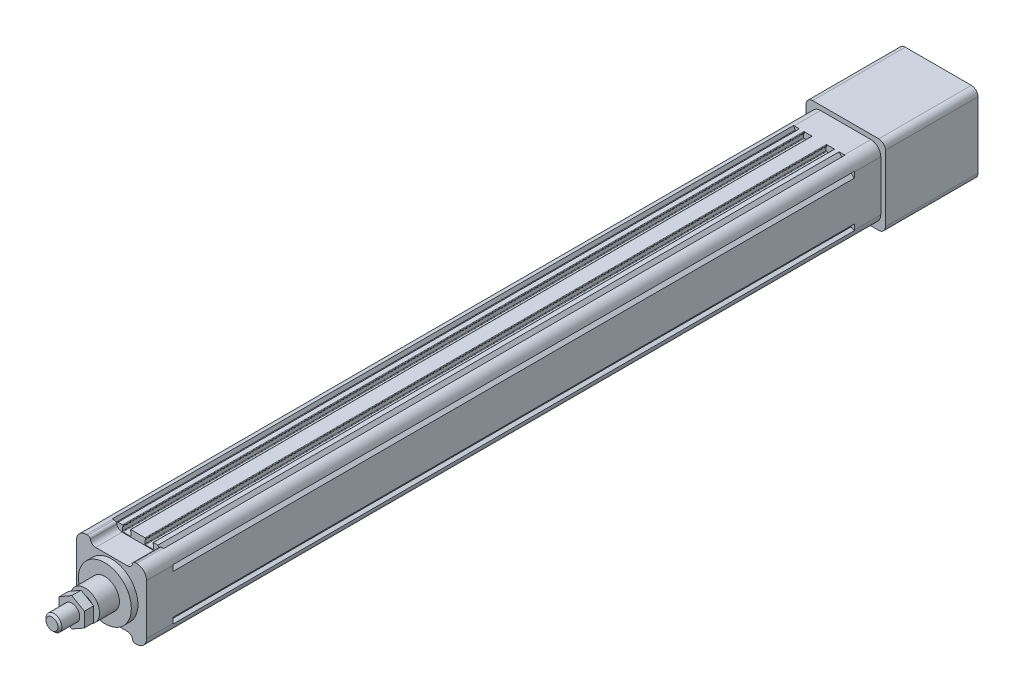
SolidWorks part; units mm, degrees
ref_plane "Front" through (0, 0, 0) normal (0, 0, 1) x (1, 0, 0)
ref_plane "Top" through (0, 0, 0) normal (0, 1, 0) x (1, 0, 0)
ref_plane "Right" through (0, 0, 0) normal (1, 0, 0) x (0, 0, -1)
sketch "草图1" plane through (0, 0, 0) normal (0, 0, 1) x (1, 0, 0)
  line L0 (19.7737, 3) -> (23.3, 3)
  line L1 (23.3, 3) -> (23.3, -3)
  line L2 (23.3, -3) -> (19.7737, -3)
  line L3 (-19.7737, -3) -> (-23.3, -3)
  line L4 (-23.3, -3) -> (-23.3, 3)
  line L5 (-23.3, 3) -> (-19.7737, 3)
  line L6 (-18.2, 24) -> (-19.4434, 26.4869)
  line L7 (-26.4869, 19.4434) -> (-24, 18.2)
  line L8 (-24, 18.2) -> (-24, 17.1)
  line L9 (-24, 17.1) -> (-26.5, 15)
  line L10 (-26.5, 15) -> (-26.5, -15)
  line L11 (-26.5, -15) -> (-24, -17.1)
  line L12 (-24, -17.1) -> (-24, -18.2)
  line L13 (-24, -18.2) -> (-26.4869, -19.4434)
  line L14 (-19.4434, -26.4869) -> (-18.2, -24)
  line L15 (-18.2, -24) -> (-17.1, -24)
  line L16 (-17.1, -24) -> (-15, -26.5)
  line L17 (-15, -26.5) -> (-11.65, -26.5)
  line L18 (-11.25, -26.1) -> (-11.25, -25.6)
  line L19 (-11.65, -25.2) -> (-11.75, -25.2)
  line L20 (-11.75, -25.2) -> (-11.75, -22.4)
  line L21 (-11.35, -22) -> (-5.65, -22)
  line L22 (-5.25, -22.4) -> (-5.25, -25.2)
  line L23 (-5.25, -25.2) -> (-5.35, -25.2)
  line L24 (-5.75, -25.6) -> (-5.75, -26.1)
  line L25 (-5.35, -26.5) -> (5.35, -26.5)
  line L26 (5.75, -26.1) -> (5.75, -25.6)
  line L27 (5.35, -25.2) -> (5.25, -25.2)
  line L28 (5.25, -25.2) -> (5.25, -22.4)
  line L29 (5.65, -22) -> (11.35, -22)
  line L30 (11.75, -22.4) -> (11.75, -25.2)
  line L31 (11.75, -25.2) -> (11.65, -25.2)
  line L32 (11.25, -25.6) -> (11.25, -26.1)
  line L33 (11.65, -26.5) -> (15, -26.5)
  line L34 (15, -26.5) -> (17.1, -24)
  line L35 (17.1, -24) -> (18.2, -24)
  line L36 (18.2, -24) -> (19.4434, -26.4869)
  line L37 (26.4869, -19.4434) -> (24, -18.2)
  line L38 (24, -18.2) -> (24, -17.1)
  line L39 (24, -17.1) -> (26.5, -15)
  line L40 (26.5, -15) -> (26.5, 15)
  line L41 (26.5, 15) -> (24, 17.1)
  line L42 (24, 17.1) -> (24, 18.2)
  line L43 (24, 18.2) -> (26.4869, 19.4434)
  line L44 (19.4434, 26.4869) -> (18.2, 24)
  line L45 (18.2, 24) -> (17.1, 24)
  line L46 (17.1, 24) -> (15, 26.5)
  line L47 (15, 26.5) -> (11.65, 26.5)
  line L48 (11.25, 26.1) -> (11.25, 25.6)
  line L49 (11.65, 25.2) -> (11.75, 25.2)
  line L50 (11.75, 25.2) -> (11.75, 22.4)
  line L51 (11.35, 22) -> (5.65, 22)
  line L52 (5.25, 22.4) -> (5.25, 25.2)
  line L53 (5.25, 25.2) -> (5.35, 25.2)
  line L54 (5.75, 25.6) -> (5.75, 26.1)
  line L55 (5.35, 26.5) -> (-5.35, 26.5)
  line L56 (-5.75, 26.1) -> (-5.75, 25.6)
  line L57 (-5.35, 25.2) -> (-5.25, 25.2)
  line L58 (-5.25, 25.2) -> (-5.25, 22.4)
  line L59 (-5.65, 22) -> (-11.35, 22)
  line L60 (-11.75, 22.4) -> (-11.75, 25.2)
  line L61 (-11.75, 25.2) -> (-11.65, 25.2)
  line L62 (-11.25, 25.6) -> (-11.25, 26.1)
  line L63 (-11.65, 26.5) -> (-15, 26.5)
  line L64 (-15, 26.5) -> (-17.1, 24)
  line L65 (-17.1, 24) -> (-18.2, 24)
  arc A0 (19.7737, 3) -> (-19.7737, 3) centre (0, 0) ccw
  arc A1 (-19.7737, -3) -> (19.7737, -3) centre (0, 0) ccw
  circle A2 centre (19, 19) radius 2.1
  circle A3 centre (19, -19) radius 2.1
  circle A4 centre (-19, -19) radius 2.1
  circle A5 centre (-19, 19) radius 2.1
  arc A6 (-19.4434, 26.4869) -> (-26.4869, 19.4434) centre (-19, 19) ccw
  arc A7 (-26.4869, -19.4434) -> (-19.4434, -26.4869) centre (-19, -19) ccw
  arc A8 (-11.65, -26.5) -> (-11.25, -26.1) centre (-11.65, -26.1) ccw
  arc A9 (-11.25, -25.6) -> (-11.65, -25.2) centre (-11.65, -25.6) ccw
  arc A10 (-11.35, -22) -> (-11.75, -22.4) centre (-11.35, -22.4) ccw
  arc A11 (-5.25, -22.4) -> (-5.65, -22) centre (-5.65, -22.4) ccw
  arc A12 (-5.35, -25.2) -> (-5.75, -25.6) centre (-5.35, -25.6) ccw
  arc A13 (-5.75, -26.1) -> (-5.35, -26.5) centre (-5.35, -26.1) ccw
  arc A14 (5.35, -26.5) -> (5.75, -26.1) centre (5.35, -26.1) ccw
  arc A15 (5.75, -25.6) -> (5.35, -25.2) centre (5.35, -25.6) ccw
  arc A16 (5.65, -22) -> (5.25, -22.4) centre (5.65, -22.4) ccw
  arc A17 (11.75, -22.4) -> (11.35, -22) centre (11.35, -22.4) ccw
  arc A18 (11.65, -25.2) -> (11.25, -25.6) centre (11.65, -25.6) ccw
  arc A19 (11.25, -26.1) -> (11.65, -26.5) centre (11.65, -26.1) ccw
  arc A20 (19.4434, -26.4869) -> (26.4869, -19.4434) centre (19, -19) ccw
  arc A21 (26.4869, 19.4434) -> (19.4434, 26.4869) centre (19, 19) ccw
  arc A22 (11.65, 26.5) -> (11.25, 26.1) centre (11.65, 26.1) ccw
  arc A23 (11.25, 25.6) -> (11.65, 25.2) centre (11.65, 25.6) ccw
  arc A24 (11.35, 22) -> (11.75, 22.4) centre (11.35, 22.4) ccw
  arc A25 (5.25, 22.4) -> (5.65, 22) centre (5.65, 22.4) ccw
  arc A26 (5.35, 25.2) -> (5.75, 25.6) centre (5.35, 25.6) ccw
  arc A27 (5.75, 26.1) -> (5.35, 26.5) centre (5.35, 26.1) ccw
  arc A28 (-5.35, 26.5) -> (-5.75, 26.1) centre (-5.35, 26.1) ccw
  arc A29 (-5.75, 25.6) -> (-5.35, 25.2) centre (-5.35, 25.6) ccw
  arc A30 (-5.65, 22) -> (-5.25, 22.4) centre (-5.65, 22.4) ccw
  arc A31 (-11.75, 22.4) -> (-11.35, 22) centre (-11.35, 22.4) ccw
  arc A32 (-11.65, 25.2) -> (-11.25, 25.6) centre (-11.65, 25.6) ccw
  arc A33 (-11.25, 26.1) -> (-11.65, 26.5) centre (-11.65, 26.1) ccw
extrude "凸台-拉伸1" add sketch "草图1" along normal blind 515
sketch "草图6" plane through (0, 0, 515) normal (0, 0, 1) x (1, 0, 0)
  line L0 (0, 0) -> (19, 0) construction
  line L2 (-26.5, -19) -> (-26.5, 19)
  line L3 (-19, 26.5) -> (-17.9161, 26.5)
  line L4 (26.5, -19) -> (26.5, 19)
  line L5 (-26.5, -26.5) -> (26.5, 26.5) construction
  line L6 (-26.5, 26.5) -> (26.5, -26.5) construction
  line L7 (-12, 21.5) -> (12, 21.5)
  line L9 (19, 26.5) -> (17.9161, 26.5)
  line L10 (19, -26.5) -> (17.9161, -26.5)
  line L11 (-12, -21.5) -> (12, -21.5)
  line L12 (-19, -26.5) -> (-17.9161, -26.5)
  arc A0 (12, 21.5) -> (15.9441, 24.8333) centre (12, 25.5) ccw
  arc A1 (-15.9441, 24.8333) -> (-12, 21.5) centre (-12, 25.5) ccw
  arc A2 (-15.9441, 24.8333) -> (-17.9161, 26.5) centre (-17.9161, 24.5) ccw
  arc A3 (15.9441, 24.8333) -> (17.9161, 26.5) centre (17.9161, 24.5) cw
  arc A4 (-26.5, -19) -> (-19, -26.5) centre (-19, -19) ccw
  arc A5 (19, -26.5) -> (26.5, -19) centre (19, -19) ccw
  arc A6 (26.5, 19) -> (19, 26.5) centre (19, 19) ccw
  arc A7 (-26.5, 19) -> (-19, 26.5) centre (-19, 19) cw
  arc A8 (15.9441, -24.8333) -> (17.9161, -26.5) centre (17.9161, -24.5) ccw
  arc A9 (12, -21.5) -> (15.9441, -24.8333) centre (12, -25.5) cw
  arc A10 (-15.9441, -24.8333) -> (-12, -21.5) centre (-12, -25.5) cw
  arc A11 (-15.9441, -24.8333) -> (-17.9161, -26.5) centre (-17.9161, -24.5) cw
  point P0 (0, 0)
  point P9 (0, 21.5)
  point P13 (20, 20.8461)
  point P16 (-12, 20.8461)
  dimension "D5" = 4
  dimension "D6" = 2
  dimension "D7" = 2
  dimension "D9" = 7.5
  dimension "D1" = 53
  dimension "D2" = 53
  dimension "D3" = 26.5
  dimension "D4" = 24
  dimension "D8" = 5
extrude "凸台-拉伸2" add sketch "草图6" along normal blind 20
sketch "草图7" plane through (0, 0, 535) normal (0, 0, 1) x (1, 0, 0)
  circle A0 centre (0, 0) radius 20
  dimension "D1" = 40
extrude "凸台-拉伸3" add sketch "草图7" along normal blind 5
sketch "草图9" plane through (0, 0, 540) normal (0, 0, 1) x (1, 0, 0)
  circle A0 centre (0, 0) radius 11
  dimension "D1" = 22
extrude "凸台-拉伸4" add sketch "草图9" along normal blind 15
sketch "草图10" plane through (0, 0, 555) normal (0, 0, 1) x (1, 0, 0)
  circle A0 centre (0, 0) radius 6
  dimension "D1" = 12
extrude "凸台-拉伸5" add sketch "草图10" along normal blind 25
sketch "草图11" plane through (0, 0, 0) normal (0, 0, -1) x (-1, 0, 0)
  line L1 (-19, -26.5) -> (19, -26.5)
  line L2 (-26.5, -19) -> (-26.5, 19)
  line L3 (-19, 26.5) -> (19, 26.5)
  line L4 (26.5, -19) -> (26.5, 19)
  line L5 (-26.5, -26.5) -> (26.5, 26.5) construction
  line L6 (-26.5, 26.5) -> (26.5, -26.5) construction
  arc A0 (-26.5, -19) -> (-19, -26.5) centre (-19, -19) ccw
  arc A1 (19, -26.5) -> (26.5, -19) centre (19, -19) ccw
  arc A2 (26.5, 19) -> (19, 26.5) centre (19, 19) ccw
  arc A3 (-26.5, 19) -> (-19, 26.5) centre (-19, 19) cw
  point P0 (0, 0)
  dimension "D3" = 7.5
  dimension "D1" = 53
  dimension "D2" = 53
extrude "凸台-拉伸6" add sketch "草图11" along normal blind 20
sketch "草图12" plane through (0, 0, -20) normal (0, 0, -1) x (-1, 0, 0)
  line L1 (-25, -30) -> (25, -30)
  line L2 (-30, -25) -> (-30, 25)
  line L3 (-25, 30) -> (25, 30)
  line L4 (30, -25) -> (30, 25)
  line L5 (-30, -30) -> (30, 30) construction
  line L6 (-30, 30) -> (30, -30) construction
  arc A0 (-30, -25) -> (-25, -30) centre (-25, -25) ccw
  arc A1 (25, -30) -> (30, -25) centre (25, -25) ccw
  arc A2 (30, 25) -> (25, 30) centre (25, 25) ccw
  arc A3 (-30, 25) -> (-25, 30) centre (-25, 25) cw
  point P0 (0, 0)
  dimension "D3" = 5
  dimension "D1" = 60
  dimension "D2" = 60
extrude "凸台-拉伸7" add sketch "草图12" along normal blind 70
sketch "草图14" plane through (0, 0, -90) normal (0, 0, -1) x (-1, 0, 0)
  circle A0 centre (0, 0) radius 19
  dimension "D1" = 38
extrude "切除-拉伸2" cut sketch "草图14" against normal blind 70
hole_wizard "M6 螺纹孔1" positions "草图15" profile "草图16" tap size "M6" standard "GB"
sketch "草图15" plane through (-26.5, 0, 0) normal (-1, 0, 0) x (0, 0, 1)
  line L0 (-20, -25) -> (-20, 25) construction
  line L1 (535, 19) -> (535, -19) construction
  point P0 (525, 11)
  point P2 (525, -11)
  point P4 (-10, 11)
  point P6 (-10, -11)
  dimension "D1" = 10
  dimension "D2" = 10
  dimension "D3" = 11
  dimension "D4" = 11
  dimension "D5" = 10
  dimension "D6" = 10
  dimension "D7" = 22
  dimension "D8" = 11
sketch "草图16" plane through (-26.5, 11, 525) normal (0, 1, 0) x (0, 0, 1)
  line L0 (0, 0) -> (0, 16.5022)
  line L1 (0, 16.5022) -> (2.5, 15)
  line L2 (2.5, 15) -> (2.5, 0)
  line L5 (2.5, 0) -> (0, 0)
  line L10 (0, 16.5022) -> (-2.5, 15) construction
  line L11 (0, -6.35) -> (0, 107.95) construction
  dimension "螺纹孔钻头直径" = 5
  dimension "螺纹孔钻头深度" = 15
  dimension "导头角度" = 118
cosmetic thread "孔螺蚊线4" parameters "D1"=12, "D2"=6
cosmetic thread "孔螺蚊线5" parameters "D1"=12, "D2"=6
cosmetic thread "孔螺蚊线6" parameters "D1"=12, "D2"=6
cosmetic thread "孔螺蚊线7" parameters "D1"=12, "D2"=6
chamfer "倒角1" distance 1.5 angle 45 1 edges at (6, 0, 580)
sketch "草图17" plane through (0, 0, 555) normal (0, 0, 1) x (1, 0, 0)
  line L1 (0, 10.9697) -> (-9.5, 5.4848)
  line L2 (-9.5, 5.4848) -> (-9.5, -5.4848)
  line L3 (-9.5, -5.4848) -> (0, -10.9697)
  line L4 (0, -10.9697) -> (9.5, -5.4848)
  line L5 (9.5, -5.4848) -> (9.5, 5.4848)
  line L6 (9.5, 5.4848) -> (0, 10.9697)
  circle A0 centre (0, 0) radius 9.5 construction
  dimension "D1" = 19
extrude "凸台-拉伸8" add sketch "草图17" along normal blind 7 from offset 3
